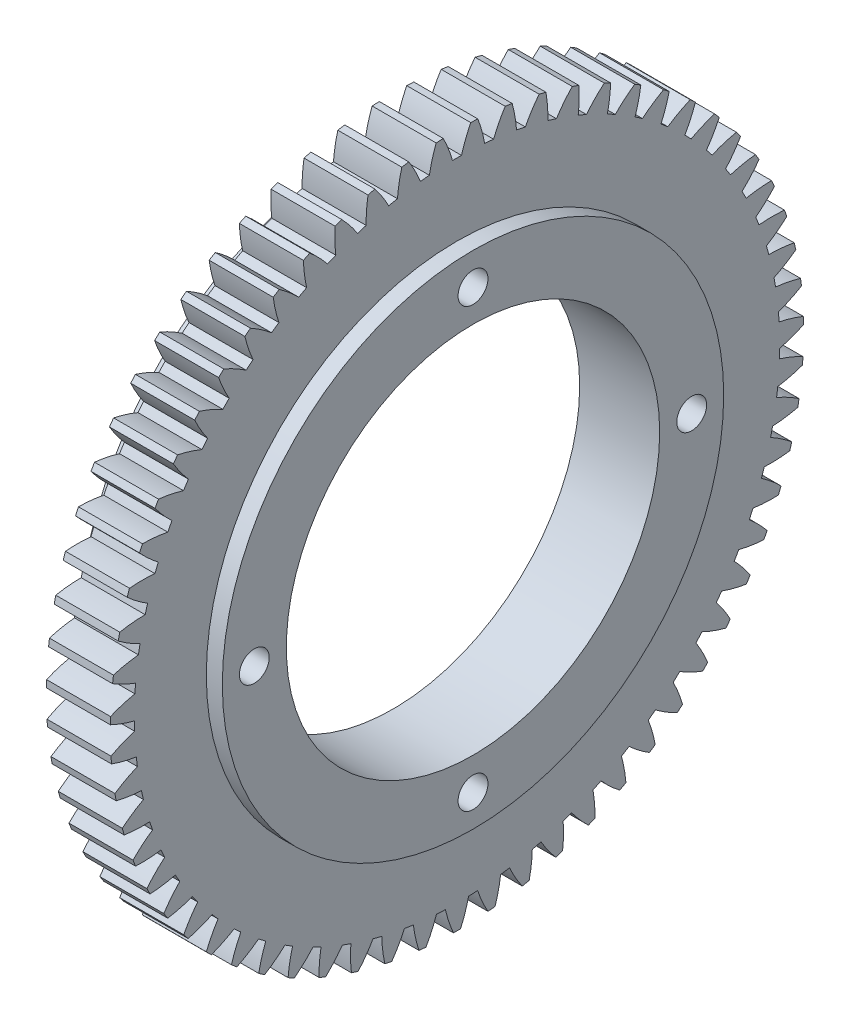
SolidWorks part; units mm, degrees
ref_plane "Plane1" through (0, 0, 0) normal (0, 0, 1) x (1, 0, 0)
ref_plane "Plane2" through (0, 0, 0) normal (0, 1, 0) x (1, 0, 0)
ref_plane "Plane3" through (0, 0, 0) normal (1, 0, 0) x (0, 0, -1)
other "Configuration Table"
sketch "HoldingSke" plane through (0, 0, 0) normal (0, 1, 0) x (1, 0, 0)
  line L0 (0, 0) -> (0.227, -0.4455)
  line L1 (-15, 0) -> (100, 0) construction
  line L2 (0, 0) -> (-2.1039, 2.3779)
  line L3 (0, 0) -> (-11.863, 4.5341)
  line L4 (0, 0) -> (3.9207, 7.6947)
  line L5 (0, 0) -> (-46.8476, -17.4728)
  line L6 (0, 0) -> (-9.9476, -6.7116)
  line L7 (-2.1039, 2.3779) -> (8.6586, 51.2059)
  line L8 (-76.2, 54.61) -> (-71.3, 54.61)
  line L9 (-71.009, 38.7566) -> (-53.1078, 45.2721)
  line L10 (-76.2, 71.12) -> (104.1128, 71.12)
  line L11 (0, 0) -> (-12, 0)
  line L12 (-76.2, 101.6) -> (-76.133, 101.6)
  line L13 (24.9733, 27.94) -> (52.9518, 28.4284)
  line L14 (24.9733, 27.94) -> (24.9743, 27.94)
  line L15 (24.9733, 27.94) -> (100.4006, 29.5858)
  line L16 (-63.627, -2) -> (-12.827, -2)
  circle A0 centre (0, 0) radius 35
  circle A1 centre (0, 0) radius 37.5
  circle A2 centre (0, 0) radius 37.5
  circle A3 centre (0, 0) radius 35
  dimension "MHD" = 75
  dimension "Hub_dia" = 75
  dimension "Bore" = 70
  dimension "MBD" = 70
  dimension "Num_teeth" = 63
  dimension "Pitch" = 0.5
  dimension "Overall_len" = 50
  dimension "Show_teeth" = 63
  dimension "Thickness" = 12
  dimension "OAL" = 50.0001
  dimension "T_dim" = 4.9
  dimension "Ap" = 20
  dimension "H" = 19.05
  dimension "Pitch_radius" = 180.3128
  dimension "Width" = 12
  dimension "Backlash" = 0.067
  dimension "Addendum_fac" = 1
  dimension "Dedendum_fac" = 1.25
  dimension "Clearance_fac" = 0.25
  dimension "Dedendum_add" = 0.001
  dimension "Module" = 2
sketch "BasProSke" plane through (0, 0, 0) normal (0, 1, 0) x (1, 0, 0)
  line L0 (-10, 0) -> (60, 0) construction
  line L1 (0, 0) -> (0, 65)
  line L2 (0, 0) -> (12, 0)
  line L3 (12, 0) -> (12, 65)
  line L4 (12, 65) -> (0, 65)
  dimension "Thickness" = 12
  dimension "Diameter" = 130
revolve "Base-Revolve" add sketch "BasProSke" angle 360 about L0
sketch "TooCutSke" plane through (0, 0, 0) normal (1, 0, 0) x (0, 0, -1)
  line L1 (0, 0) -> (0, 107) construction
  line L2 (0, 0) -> (-1.6879, 62.9774) construction
  line L3 (0, 0) -> (-6.2789, 125.8099) construction
  line L4 (-1.6879, 62.9774) -> (-3.1395, 62.9049) construction
  arc A0 (0.8418, 60.4931) -> (-0.8418, 60.4931) centre (0, 0) ccw
  arc A1 (2.5886, 64.9739) -> (-2.5886, 64.9739) centre (0, 0) ccw
  circle A2 centre (0, 0) radius 63 construction
  circle A3 centre (0, 0) radius 59.2006 construction
  arc A4 (-0.8418, 60.4931) -> (-2.5886, 64.9739) centre (-25.0871, 53.6223) ccw
  arc A5 (2.5886, 64.9739) -> (0.8418, 60.4931) centre (25.0871, 53.6223) ccw
  dimension "Root_dia" = 120.998
  dimension "Overcut_dia" = 130.0508
  dimension "Pitch_dia" = 126
  dimension "Base_dia" = 118.4013
  dimension "Flank_rad" = 25.2
  dimension "Half_ang" = 2.857
  dimension "Half_CT" = 1.4534
extrude "ToothCut" cut sketch "TooCutSke" along normal through all
fillet "Breaks" [suppressed] radius 0.04
fillet "RootFillets" [suppressed] radius 0.501
pattern_circular "TeethCuts" count 63 every 5.714 about axis through (-10, 0, 0) along (1, 0, 0) of "ToothCut", "RootFillets", "Breaks"
sketch "HubNeaOneSke" plane through (0, 0, 0) normal (-1, 0, 0) x (0, 0, 1)
  circle A0 centre (0, 0) radius 37.5
  dimension "Diameter" = 75
extrude "HubNearOne" [suppressed] add sketch "HubNeaOneSke" along normal blind 38.0001
sketch "HubNeaBotSke" plane through (0, 0, 0) normal (-1, 0, 0) x (0, 0, 1)
  circle A0 centre (0, 0) radius 37.5
  dimension "Diameter" = 75
extrude "HubNearBoth" [suppressed] add sketch "HubNeaBotSke" along normal blind 19
ref_plane "FarPln" through (12, 0, 0) normal (1, 0, 0) x (0, 0, -1)
sketch "HubFarSke" plane through (12, 0, 0) normal (1, 0, 0) x (0, 0, -1)
  circle A0 centre (0, 0) radius 37.5
  dimension "Diameter" = 75
extrude "HubFar" [suppressed] add sketch "HubFarSke" along normal blind 19
sketch "BorSke" plane through (0, 0, 0) normal (1, 0, 0) x (0, 0, -1)
  circle A0 centre (0, 0) radius 35
  dimension "Diameter" = 70
extrude "Bore" cut sketch "BorSke" along normal mid plane 100.0001
sketch "KeySke" plane through (0, 0, 0) normal (1, 0, 0) x (0, 0, -1)
  line L0 (-10, 0) -> (-10, 39.9)
  line L1 (-10, 39.9) -> (10, 39.9)
  line L2 (10, 39.9) -> (10, 0)
  line L3 (0, 0) -> (0, 34) construction
  line L4 (-10, 0) -> (10, 0)
  dimension "Offset" = 39.9
  dimension "Width" = 20
extrude "Keyway" [suppressed] cut sketch "KeySke" along normal mid plane 100.0001
pattern_circular "Keyway2" [suppressed] count 2 every 90 about axis through (-10, 0, 0) along (1, 0, 0)
sketch "Schizzo1" plane through (12, 0, 0) normal (1, 0, 0) x (0, 0, -1)
  circle A0 centre (0, 0) radius 47
  circle A1 centre (0, 0) radius 35
  dimension "D1" = 94
  dimension "D2" = 70
extrude "Estrusione-Estrusione1" add sketch "Schizzo1" along normal blind 3
sketch "Schizzo2" plane through (0, 0, 0) normal (-1, 0, 0) x (0, 0, 1)
  circle A0 centre (0, 0) radius 50
  circle A1 centre (0, 0) radius 53
  dimension "D1" = 100
  dimension "D2" = 3
extrude "Estrusione-Estrusione2" add sketch "Schizzo2" along normal blind 6
sketch "Schizzo3" plane through (15, 0, 0) normal (1, 0, 0) x (0, 0, -1)
  line L0 (-41, 0) -> (41, 0) construction
  line L2 (0, -41) -> (0, 41) construction
  circle A0 centre (0, 0) radius 41 construction
  point P0 (0, 41)
  point P2 (-41, 0)
  point P4 (41, 0)
  point P6 (0, -41)
  point P22 (2.055, -41.6361)
  point P23 (0, 0)
  point P24 (0, 41.5552)
  dimension "D1" = 82
hole_wizard "Foro per Vite M3-1" positions "Schizzo3" profile "Schizzo4" hole size "M3" standard "ISO"
sketch "Schizzo4" plane through (15, 41, 0) normal (0, 1, 0) x (0, 0, -1)
  line L0 (0, 0) -> (0, 9.7824)
  line L1 (0, 9.7824) -> (2.8, 8.1)
  line L2 (2.8, 8.1) -> (2.8, 0)
  line L5 (2.8, 0) -> (0, 0)
  line L10 (0, 9.7824) -> (-2.8, 8.1) construction
  line L11 (0, -6.35) -> (0, 107.95) construction
  dimension "Hole Dia." = 5.6
  dimension "Hole Depth" = 8.1
  dimension "Drill Angle" = 118
equation "' \"Module@HoldingSke\" = 6.35"
equation "' \"Num_teeth@HoldingSke\" = 12"
equation "' \"Ap@HoldingSke\" =  20"
equation "' \"Ap@HoldingSke\" = 20"
equation "' \"Width@HoldingSke\" = 0.5 * 25.4"
equation "' \"Hub_dia@HoldingSke\"= 1 * 25.4"
equation "' \"Hub_dia@HoldingSke\" = 1 * 25.4"
equation "' \"Overall_len@HoldingSke\" = 1.0 * 25.4"
equation "' \"Bore@HoldingSke\" = 0.75 * 25.4"
equation "' \"T_dim@HoldingSke\" = 0.1 * 25.4"
equation "' \"Width@KeySke\" = 0.25 * 25.4"
equation "' \"Show_teeth@HoldingSke\" = 13"
equation "' \"Backlash@HoldingSke\" = 0.009 * 25.4"
equation "' \"Addendum_fac@HoldingSke\" = 1.0"
equation "' \"Dedendum_fac@HoldingSke\" = 1.25"
equation "' \"Dedendum_add@HoldingSke\" = 0.00005 * 25.4"
equation "' \"Clearance_fac@HoldingSke\" = 0.25"
equation "\"Pitch@HoldingSke\" = 1 / \"Module@HoldingSke\""
equation "\"Overcut_dia@TooCutSke\" = (\"Num_teeth@HoldingSke\" + 2 * \"Addendum_fac@HoldingSke\") / \"Pitch@HoldingSke\" + 0.002 * 25.4"
equation "\"Pitch_dia@TooCutSke\" = \"Num_teeth@HoldingSke\" / \"Pitch@HoldingSke\""
equation "\"Base_dia@TooCutSke\" = \"Num_teeth@HoldingSke\" / \"Pitch@HoldingSke\" * cos((\"Ap@HoldingSke\"  * 3.14159265 / 180))"
equation "\"Root_dia@TooCutSke\" = (\"Num_teeth@HoldingSke\" + 2) / \"Pitch@HoldingSke\" - 2 * (\"Addendum_fac@HoldingSke\" + \"Dedendum_fac@HoldingSke\") / \"Pitch@HoldingSke\" - \"Dedendum_add@HoldingSke\" * 2"
equation "\"Half_ang@TooCutSke\" = 180 / \"Num_teeth@HoldingSke\""
equation "\"Half_CT@TooCutSke\" = \"Num_teeth@HoldingSke\" / \"Pitch@HoldingSke\" * sin((3.14159265 / 2 / \"Num_teeth@HoldingSke\")) / 2 - 7 * \"Backlash@HoldingSke\" / 4"
equation "\"Flank_rad@TooCutSke\" = \"Num_teeth@HoldingSke\" / \"Pitch@HoldingSke\" / 5"
equation "\"Radius@RootFillets\" = \"Clearance_fac@HoldingSke\" / \"Pitch@HoldingSke\" + \"Dedendum_add@HoldingSke\""
equation "\"Break_rad@Breaks\" = 0.02 / \"Pitch@HoldingSke\""
equation "\"Thickness@HoldingSke\" = \"Width@HoldingSke\""
equation "\"OAL@HoldingSke\" = \"Thickness@HoldingSke\""
equation "\"MHD@HoldingSke\" = (\"Num_teeth@HoldingSke\" + 2) / \"Pitch@HoldingSke\" - 2 * (\"Addendum_fac@HoldingSke\" + \"Dedendum_fac@HoldingSke\")  / \"Pitch@HoldingSke\" - \"Dedendum_add@HoldingSke\" * 2"
equation "\"MBD@HoldingSke\" = (\"Num_teeth@HoldingSke\" + 2) / \"Pitch@HoldingSke\" - 2 * (\"Addendum_fac@HoldingSke\" + \"Dedendum_fac@HoldingSke\")  / \"Pitch@HoldingSke\" - \"Dedendum_add@HoldingSke\" * 2 - 0.002 * 25.4"
equation "\"MHD@HoldingSke\" = ((sgn( \"MHD@HoldingSke\" - \"Hub_dia@HoldingSke\" )-1)*( \"MHD@HoldingSke\" - \"Hub_dia@HoldingSke\" ))/-2+ \"Hub_dia@HoldingSke\""
equation "\"MBD@HoldingSke\" = ((sgn( \"MBD@HoldingSke\" - \"Bore@HoldingSke\" )-1)*( \"MBD@HoldingSke\" - \"Bore@HoldingSke\" ))/-2+ \"Bore@HoldingSke\""
equation "\"OAL@HoldingSke\" = ((sgn( \"OAL@HoldingSke\" - \"Overall_len@HoldingSke\" )+1)*( \"OAL@HoldingSke\" - \"Overall_len@HoldingSke\" ))/2 + \"Overall_len@HoldingSke\" + 0.000002 * 25.4"
equation "\"Num_teeth@TeethCuts\" = int( \"Show_teeth@HoldingSke\" ) + 1"
equation "\"Num_teeth@TeethCuts\" = ((sgn( \"Num_teeth@TeethCuts\" - \"Num_teeth@HoldingSke\" )-1)*( \"Num_teeth@TeethCuts\" - \"Num_teeth@HoldingSke\" ))/-2+ \"Num_teeth@HoldingSke\""
equation "\"Num_teeth@TeethCuts\" = ((sgn( \"Num_teeth@TeethCuts\" - 2.0)+1)*( \"Num_teeth@TeethCuts\" - 2.0))/2 +2.0"
equation "\"Angle@TeethCuts\" = 360.0 / \"Num_teeth@HoldingSke\""
equation "\"Diameter@BasProSke\" = (\"Num_teeth@HoldingSke\" + 2 * \"Addendum_fac@HoldingSke\") / \"Pitch@HoldingSke\""
equation "\"Thickness@BasProSke\"  = \"Thickness@HoldingSke\""
equation "' \"Fillet_rad@BasProSke\" =  \"Thickness@HoldingSke\" * 0.05"
equation "' \"Fillet_rad@BasProSke\" = \"Thickness@HoldingSke\" * 0.05"
equation "\"MHD@HoldingSke\" = ((sgn( \"MHD@HoldingSke\" - \"Root_dia@TooCutSke\" )-1)*( \"MHD@HoldingSke\" - \"Root_dia@TooCutSke\" ))/-2+ \"Root_dia@TooCutSke\""
equation "\"Diameter@HubNeaOneSke\" = \"MHD@HoldingSke\""
equation "\"Length@HubNearOne\" = \"OAL@HoldingSke\" - \"Thickness@BasProSke\""
equation "\"Diameter@HubNeaBotSke\" = \"MHD@HoldingSke\""
equation "\"Length@HubNearBoth\" = ( \"OAL@HoldingSke\" - \"Thickness@BasProSke\" ) / 2.0"
equation "\"Thickness@FarPln\" = \"Thickness@BasProSke\""
equation "\"Diameter@HubFarSke\" = \"MHD@HoldingSke\""
equation "\"Length@HubFar\" = ( \"OAL@HoldingSke\" - \"Thickness@BasProSke\" ) / 2.0"
equation "\"Diameter@BorSke\" = \"MBD@HoldingSke\""
equation "\"D1@Bore\" = \"OAL@HoldingSke\" * 2.0"
equation "\"D1@Keyway\" = \"OAL@HoldingSke\" * 2.0"
equation "\"Offset@KeySke\" = \"T_dim@HoldingSke\" + \"MBD@HoldingSke\" / 2.0"
